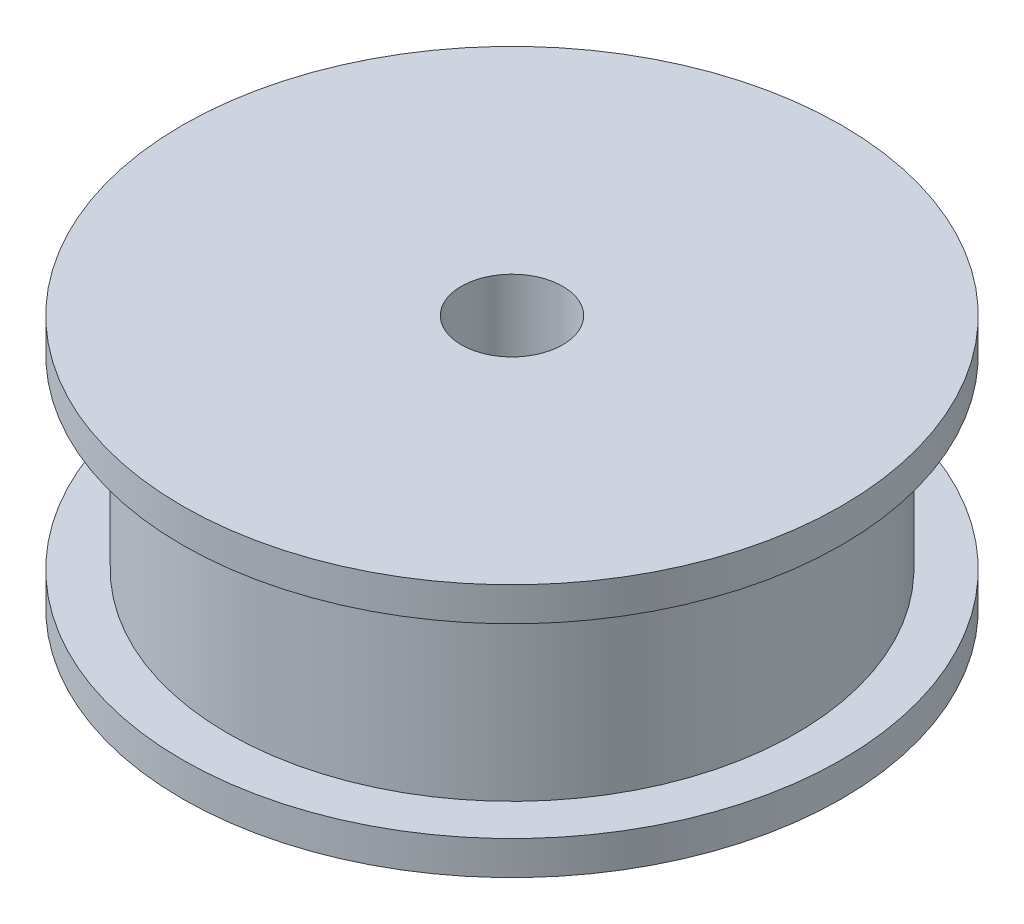
SolidWorks part; units mm, degrees
ref_plane "Front" through (0, 0, 0) normal (0, 0, 1) x (1, 0, 0)
ref_plane "Top" through (0, 0, 0) normal (0, 1, 0) x (1, 0, 0)
ref_plane "Right" through (0, 0, 0) normal (1, 0, 0) x (0, 0, -1)
sketch "草图1" plane through (0, 0, 0) normal (0, 0, 1) x (1, 0, 0)
  line L0 (0, 0) -> (19.5, 0)
  line L1 (0, 23.5758) -> (0, -15.2121) construction
  line L2 (19.5, 0) -> (19.5, -2)
  line L3 (19.5, -2) -> (16.805, -2)
  line L4 (16.805, -2) -> (16.805, -13)
  line L5 (16.805, -13) -> (19.5, -13)
  line L6 (19.5, -13) -> (19.5, -15)
  line L7 (19.5, -15) -> (0, -15)
  line L8 (0, 0) -> (0, -15)
  dimension "D1" = 2
  dimension "D2" = 2
  dimension "D3" = 11
  dimension "D4" = 19.5
  dimension "D5" = 33.61
  dimension "D6" = 19.5
revolve "旋转1" add sketch "草图1" angle 360 about L1
sketch "草图2" plane through (0, 0, 0) normal (0, 1, 0) x (1, 0, 0)
  circle A0 centre (0, 0) radius 3
  dimension "D1" = 6
extrude "切除-拉伸1" cut sketch "草图2" against normal through all
